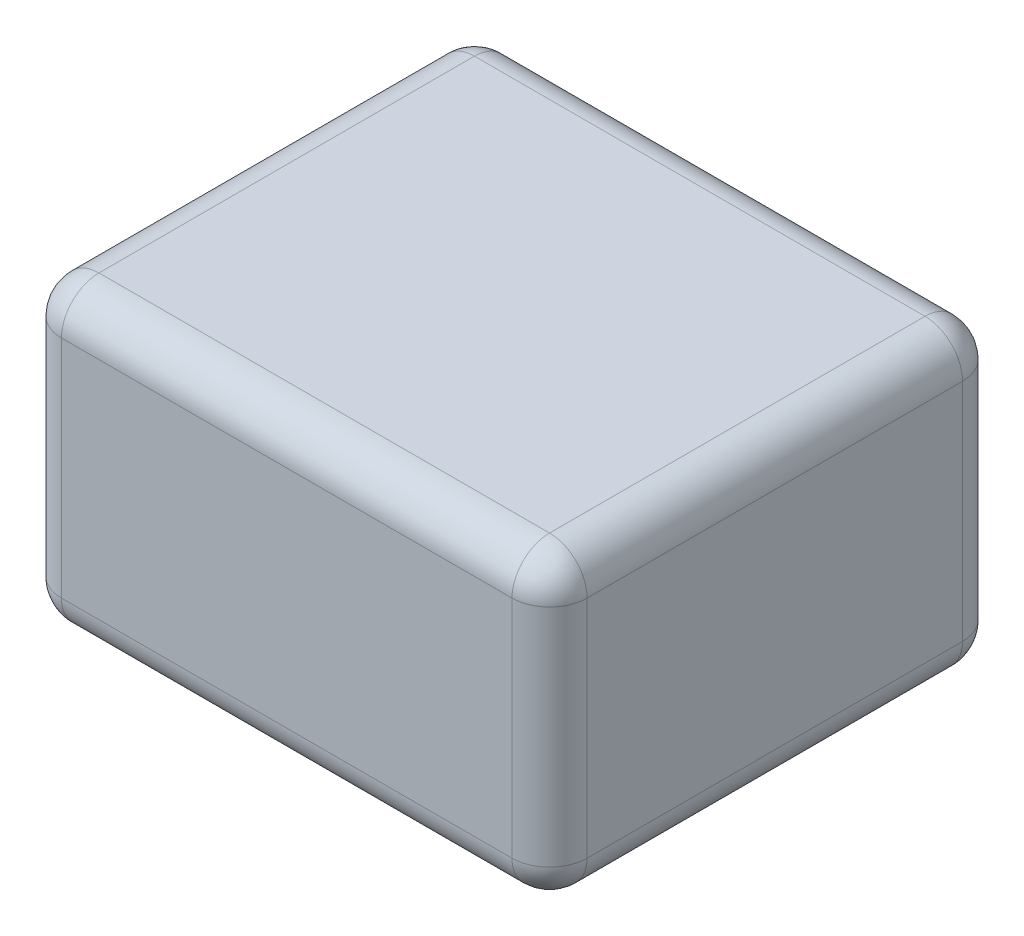
SolidWorks part; units mm, degrees
ref_plane "Front Plane" through (0, 0, 0) normal (0, 0, 1) x (1, 0, 0)
ref_plane "Top Plane" through (0, 0, 0) normal (0, 1, 0) x (1, 0, 0)
ref_plane "Right Plane" through (0, 0, 0) normal (1, 0, 0) x (0, 0, -1)
sketch "Sketch1" plane through (0, 0, 0) normal (0, 1, 0) x (1, 0, 0)
  line L1 (-35, 30) -> (35, 30)
  line L2 (-35, 30) -> (-35, -30)
  line L3 (-35, -30) -> (35, -30)
  line L4 (35, 30) -> (35, -30)
  line L5 (-35, 30) -> (35, -30) construction
  line L6 (-35, -30) -> (35, 30) construction
  point P0 (0, 0)
  dimension "D1" = 70
  dimension "D2" = 60
extrude "Boss-Extrude1" add sketch "Sketch1" along normal blind 40
fillet "Fillet1" radius 5 12 edges at (-35, 0, 0) (-35, 20, -30) (0, 0, -30) (35, 20, -30) (35, 0, 0) (-35, 20, 30) (35, 20, 30) (0, 0, 30) (0, 40, 30) (-35, 40, 0) (0, 40, -30) (35, 40, 0)
